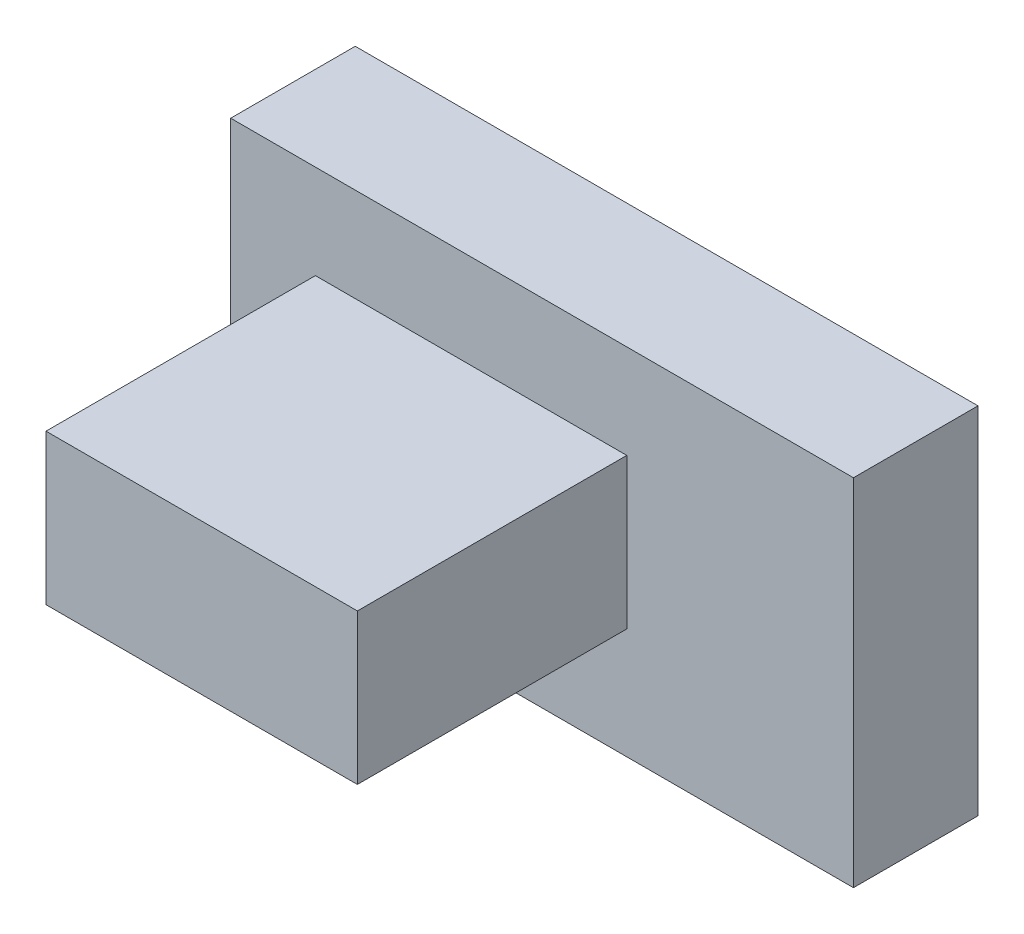
SolidWorks part; units mm, degrees
ref_plane "Front Plane" through (0, 0, 0) normal (0, 0, 1) x (1, 0, 0)
ref_plane "Top Plane" through (0, 0, 0) normal (0, 1, 0) x (1, 0, 0)
ref_plane "Right Plane" through (0, 0, 0) normal (1, 0, 0) x (0, 0, -1)
sketch "square" plane through (0, 0, 0) normal (0, 0, 1) x (1, 0, 0)
  line L0 (0, 0) -> (127, 0)
  line L1 (0, 0) -> (0, 72.4073)
  line L2 (0, 72.4073) -> (127, 72.4073)
  line L3 (127, 72.4073) -> (127, 0)
  point P1 (0, 0)
  point P5 (0, 0)
  dimension "D1" = 127
  dimension "D2" = 72.4073
  dimension "D3" = 72.4073
  dimension "D4" = 127
extrude "Boss-Extrude4" add sketch "square" along normal blind 25.4
sketch "Sketch3" plane through (0, 0, 25.4) normal (0, 0, 1) x (1, 0, 0)
  line L0 (17.2719, 53.2383) -> (17.2719, 22.5905)
  line L1 (17.2719, 22.5905) -> (80.7719, 22.5905)
  line L2 (80.7719, 22.5905) -> (80.7719, 53.2383)
  line L3 (80.7719, 53.2383) -> (17.2719, 53.2383)
  dimension "D1" = 63.5
  dimension "D2" = 63.5
extrude "Boss-Extrude5" add sketch "Sketch3" along normal blind 54.9384
